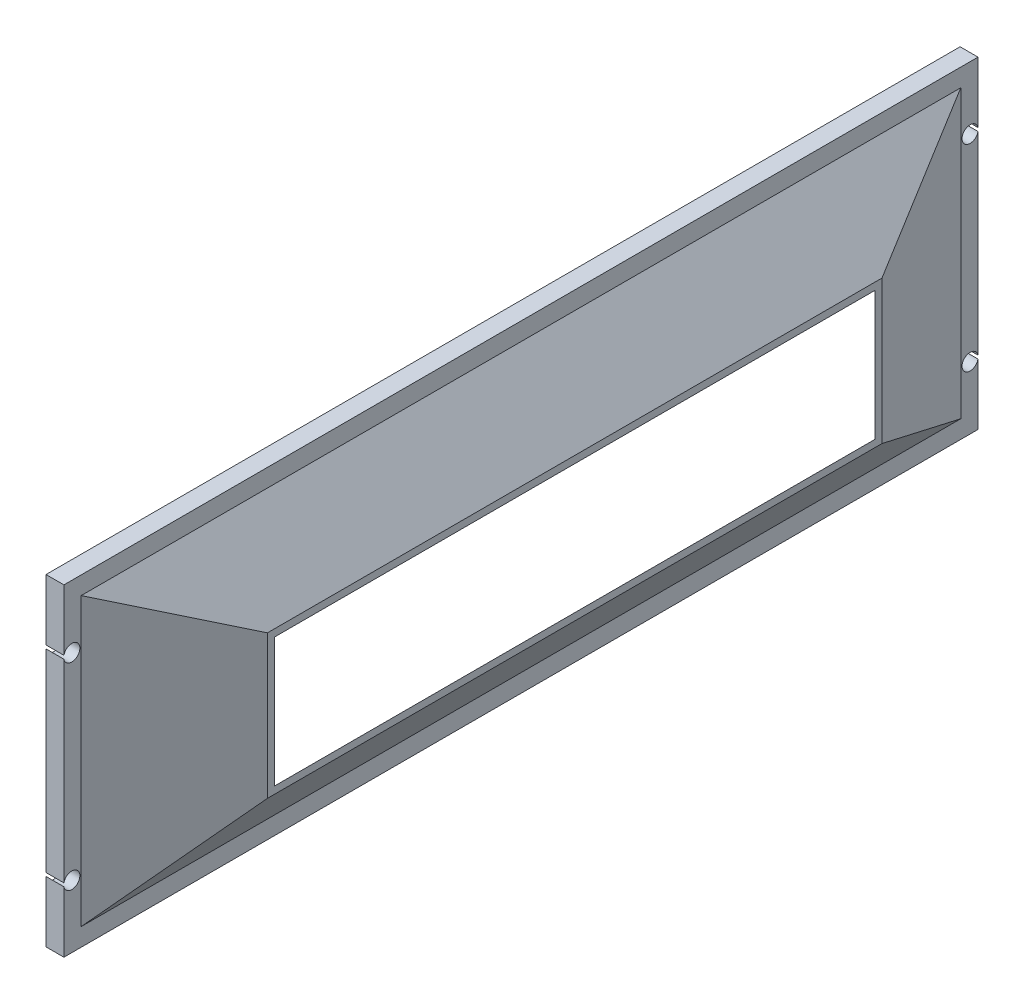
SolidWorks part; units mm, degrees
ref_plane "Front Plane" through (0, 0, 0) normal (0, 0, 1) x (1, 0, 0)
ref_plane "Top Plane" through (0, 0, 0) normal (0, 1, 0) x (1, 0, 0)
ref_plane "Right Plane" through (0, 0, 0) normal (1, 0, 0) x (0, 0, -1)
sketch "Sketch1" plane through (0, 0, 0) normal (1, 0, 0) x (0, 0, -1)
  line L1 (-120.75, -38) -> (120.75, -38)
  line L2 (-120.75, -38) -> (-120.75, 38)
  line L3 (-120.75, 38) -> (120.75, 38)
  line L4 (120.75, -38) -> (120.75, 38)
  line L5 (-120.75, -38) -> (120.75, 38) construction
  line L6 (-120.75, 38) -> (120.75, -38) construction
  line L7 (-127.55, -45) -> (127.55, -45)
  line L8 (-127.55, -45) -> (-127.55, 45)
  line L9 (-127.55, 45) -> (127.55, 45)
  line L10 (127.55, -45) -> (127.55, 45)
  line L11 (-127.55, -45) -> (127.55, 45) construction
  line L12 (-127.55, 45) -> (127.55, -45) construction
  point P0 (0, 0)
  point P6 (0, 0)
  point P11 (0, 0)
  dimension "D1" = 90
  dimension "D2" = 241.5
  dimension "D3" = 6.8
  dimension "D4" = 7
extrude "Boss-Extrude1" add sketch "Sketch1" along normal blind 5
sketch "Sketch3" plane through (0, -38, 0) normal (0, 1, 0) x (1, 0, 0)
  line L0 (5, 120.75) -> (20, 83.75)
  line L1 (20, 83.75) -> (20, 85.75)
  line L2 (20, 85.75) -> (5, 122.75)
  line L3 (5, 120.75) -> (5, 122.75)
  dimension "D1" = 2
  dimension "D2" = 15
  dimension "D3" = 35
extrude "Boss-Extrude2" add sketch "Sketch3" along normal blind 78
sketch "Sketch6" plane through (0, -38, 0) normal (0, -1, 0) x (1, 0, 0)
  line L0 (5, -122.75) -> (20, -85.75)
  line L1 (20, -85.75) -> (20, -83.75)
  line L2 (20, -83.75) -> (5, -120.75)
  line L3 (5, -120.75) -> (5, -122.75)
extrude "Boss-Extrude3" add sketch "Sketch6" along normal blind 2
mirror "Mirror1" about plane through (0, 0, 0) normal (0, 0, 1) of "Boss-Extrude3", "Boss-Extrude2"
sketch "Sketch7" plane through (0, 0, -120.75) normal (0, 0, 1) x (1, 0, 0)
  line L0 (5, 38) -> (20, 18)
  line L1 (20, 18) -> (20, 20)
  line L2 (20, 20) -> (5, 40)
  line L3 (5, 40) -> (5, 38)
  line L4 (11, 0) -> (-11, 0) construction
  line L5 (5, -40) -> (5, -38)
  line L6 (20, -20) -> (5, -40)
  line L7 (20, -18) -> (20, -20)
  line L8 (5, -38) -> (20, -18)
  line L9 (20, 40) -> (20, -40) construction
  dimension "D2" = 20
extrude "Boss-Extrude4" add sketch "Sketch7" along normal up to vertex (241.5 mm away)
sketch "Sketch8" plane through (0, -45, 0) normal (0, -1, 0) x (1, 0, 0)
  line L0 (20, -120.75) -> (5.8108, -120.75)
  line L1 (5.8108, -120.75) -> (20, -85.75)
  line L2 (20, -85.75) -> (20, -120.75)
  line L3 (5.8108, 120.75) -> (20, 120.75)
  line L4 (20, 120.75) -> (20, 85.75)
  line L5 (20, 85.75) -> (5.8108, 120.75)
extrude "Cut-Extrude1" cut sketch "Sketch8" against normal blind 141
sketch "Sketch9" plane through (0, 0, 0) normal (0, 0, 1) x (1, 0, 0)
  line L1 (5, 40) -> (20, 20)
  line L2 (5, 40) -> (20, 40)
  line L3 (20, 40) -> (20, 20)
extrude "Cut-Extrude2" cut sketch "Sketch9" against normal blind 141 and the other way blind 141
mirror "Mirror5" about plane through (0, 0, 0) normal (0, 1, 0) of "Cut-Extrude2"
hole_wizard "M4 Clearance Hole1" positions "Sketch10" profile "Sketch12" hole size "M4" standard "ANSI Metric" end condition through all
sketch "Sketch10" plane through (5, 0, 0) normal (1, 0, 0) x (0, 0, -1)
  line L0 (-125.35, 27.5) -> (-125.35, -27.5)
  line L2 (-127.55, 45) -> (-127.55, -45) construction
  point P1 (-125.35, 27.5)
  point P2 (-125.35, -27.5)
  point P5 (-125.35, 0)
  dimension "D1" = 55
  dimension "D2" = 2.2
sketch "Sketch12" plane through (5, 27.5, 125.35) normal (0, 1, 0) x (0, 0, -1)
  line L0 (0, 0) -> (0, 5)
  line L1 (0, 5) -> (2.25, 5)
  line L2 (2.25, 5) -> (2.25, 0)
  line L5 (2.25, 0) -> (0, 0)
  line L11 (0, -6.35) -> (0, 107.95) construction
  dimension "Thru Hole Dia." = 4.5
  dimension "Thru Hole Depth" = 5
mirror "Mirror6" about plane through (0, 0, 0) normal (0, 0, 1) of "M4 Clearance Hole1"
